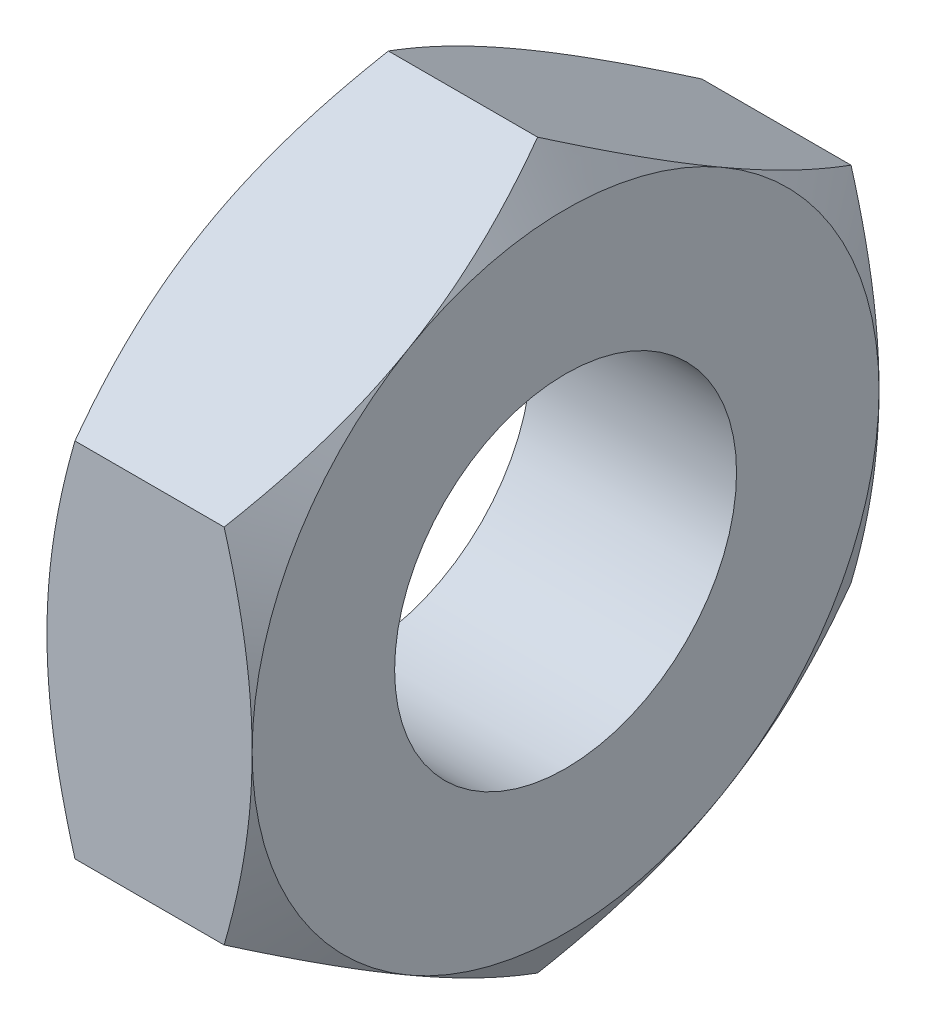
SolidWorks part; units mm, degrees
material "Chrome Stainless Steel"
ref_plane "Front Plane" through (0, 0, 0) normal (0, 0, 1) x (1, 0, 0)
ref_plane "Top Plane" through (0, 0, 0) normal (0, 1, 0) x (1, 0, 0)
ref_plane "Right Plane" through (0, 0, 0) normal (1, 0, 0) x (0, 0, -1)
sketch "Sketch1" plane through (0, 0, 0) normal (1, 0, 0) x (0, 0, -1)
  line L1 (0, 3.1754) -> (-2.75, 1.5877)
  line L2 (-2.75, 1.5877) -> (-2.75, -1.5877)
  line L3 (-2.75, -1.5877) -> (0, -3.1754)
  line L4 (0, -3.1754) -> (2.75, -1.5877)
  line L5 (2.75, -1.5877) -> (2.75, 1.5877)
  line L6 (2.75, 1.5877) -> (0, 3.1754)
  circle A0 centre (0, 0) radius 2.75 construction
extrude "Boss-Extrude1" add sketch "Sketch1" against normal blind 2.4
sketch "Sketch2" plane through (0, 0, 0) normal (0, 0, 1) x (1, 0, 0)
  line L0 (-2.2385, 0) -> (0.6157, 0) construction
  line L1 (-2.4, 2.75) -> (-2.1544, 3.1754)
  line L2 (-2.4, 3.1754) -> (-2.4, 1.5877) construction
  line L3 (-2.4, 3.1754) -> (0, 3.1754) construction
  line L4 (-2.1544, 3.1754) -> (-2.4, 3.1754)
  line L5 (-2.4, 3.1754) -> (-2.4, 2.75)
revolve "Cut-Revolve1" cut sketch "Sketch2" about L0
sketch "Sketch5" plane through (0, 0, 0) normal (0, 0, 1) x (1, 0, 0)
  line L0 (0, 0) -> (-2.4, 0) construction
  line L1 (-2.1544, 3.1754) -> (0, 3.1754) construction
  line L2 (-2.4, 0) -> (-1.8, 0)
  line L3 (-2.4, 0) -> (-2.4, 3.1754)
  line L4 (-2.4, 3.1754) -> (-1.8, 3.1754)
  line L5 (-1.8, 0) -> (-1.8, 3.1754)
  dimension "T1" = 1.8
revolve "Cut-Revolve2" cut sketch "Sketch5" about L0
sketch "Sketch6" plane through (0, 0, 0) normal (0, 0, 1) x (1, 0, 0)
  line L0 (-1.8, 2.75) -> (-1.5544, 3.1754)
  line L1 (-1.8, 0) -> (-1.8, 3.1754) construction
  line L2 (-2.4, 3.1754) -> (-1.8, 3.1754) construction
  line L3 (-1.5544, 3.1754) -> (-1.8, 3.1754)
  line L4 (-1.8, 3.1754) -> (-1.8, 2.75)
  line L5 (0, 2.75) -> (-0.2456, 3.1754)
  line L6 (0, 3.1754) -> (0, 1.5877) construction
  line L7 (-0.2456, 3.1754) -> (0, 3.1754)
  line L8 (0, 3.1754) -> (0, 2.75)
  line L9 (-1.687, 0) -> (0.4573, 0) construction
revolve "Cut-Revolve3" cut sketch "Sketch6" about L9
sketch "Sketch7" plane through (0, 0, 0) normal (1, 0, 0) x (0, 0, -1)
  circle A0 centre (0, 0) radius 1.5
  dimension "D1" = 3
extrude "Cut-Extrude1" cut sketch "Sketch7" against normal through all
equation "\"Factor\"= 1.082532"
equation "\"M\"=3.000000"
equation "\"Pitch\"=0.5"
equation "\"STD\"= round ( \"M\" - \"Factor\" * \"Pitch\" , 3 )"
